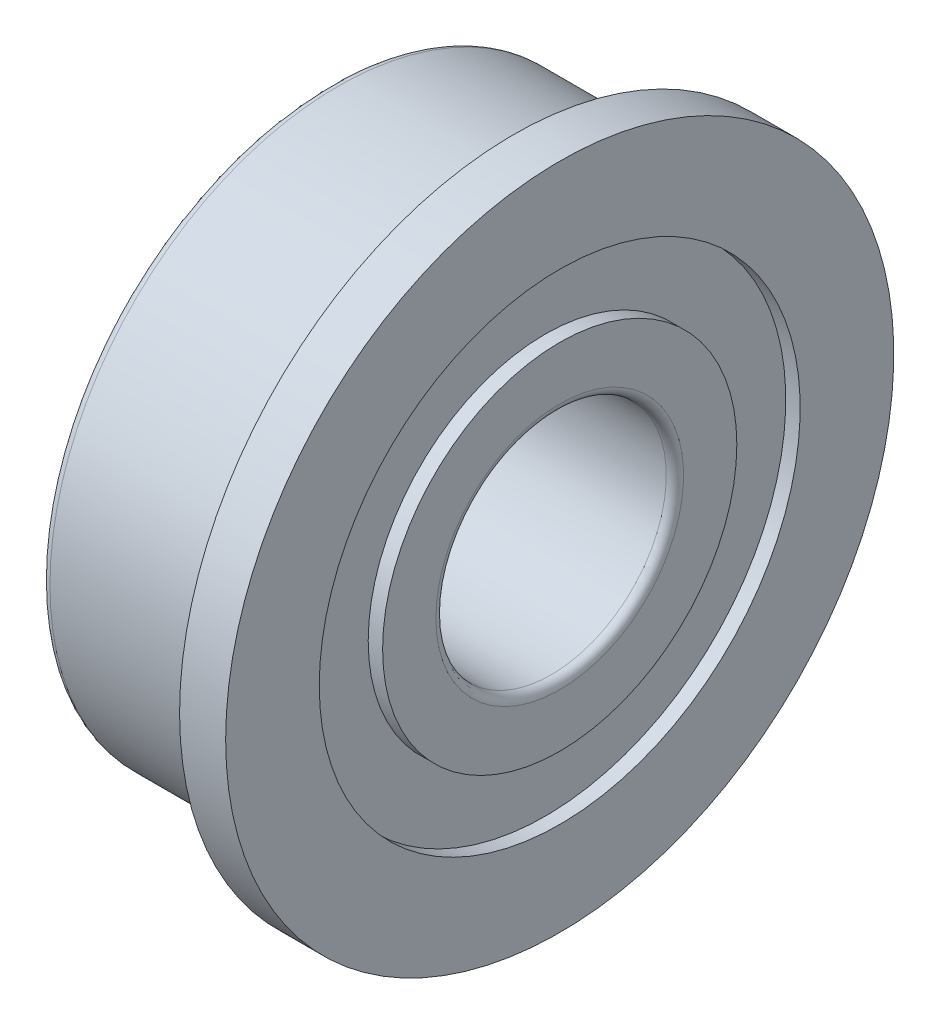
SolidWorks part; units mm, degrees
ref_plane "Front Plane" through (0, 0, 0) normal (0, 0, 1) x (1, 0, 0)
ref_plane "Top Plane" through (0, 0, 0) normal (0, 1, 0) x (1, 0, 0)
ref_plane "Right Plane" through (0, 0, 0) normal (1, 0, 0) x (0, 0, -1)
ref_plane "Plane1" through (0, 0, 0) normal (0, 0, 1) x (1, 0, 0)
sketch "Sketch1" plane through (0, 0, 0) normal (0, 0, 1) x (1, 0, 0)
  line L0 (0, 4.85) -> (0, 4.175)
  line L1 (0, 4.175) -> (0.25, 4.175)
  line L2 (0.25, 4.175) -> (0.25, 3.075)
  line L3 (0.25, 3.075) -> (0, 3.075)
  line L4 (0, 3.075) -> (0, 2.15)
  line L5 (0.15, 2) -> (3.85, 2)
  line L6 (4, 2.15) -> (4, 3.075)
  line L7 (4, 3.075) -> (3.75, 3.075)
  line L8 (3.75, 3.075) -> (3.75, 4.175)
  line L9 (3.75, 4.175) -> (4, 4.175)
  line L10 (4, 4.175) -> (4, 5.8)
  line L11 (4, 5.8) -> (3.2, 5.8)
  line L12 (3.2, 5.8) -> (3.2, 5.2)
  line L13 (3, 5) -> (0.15, 5)
  line L14 (10, 0) -> (-10, 0) construction
  arc A0 (0, 2.15) -> (0.15, 2) centre (0.15, 2.15) ccw
  arc A1 (3.85, 2) -> (4, 2.15) centre (3.85, 2.15) ccw
  arc A2 (3.2, 5.2) -> (3, 5) centre (3.2, 5) cw
  arc A3 (0.15, 5) -> (0, 4.85) centre (0.15, 4.85) ccw
revolve "Revolve1" add sketch "Sketch1" angle 360 about L14
